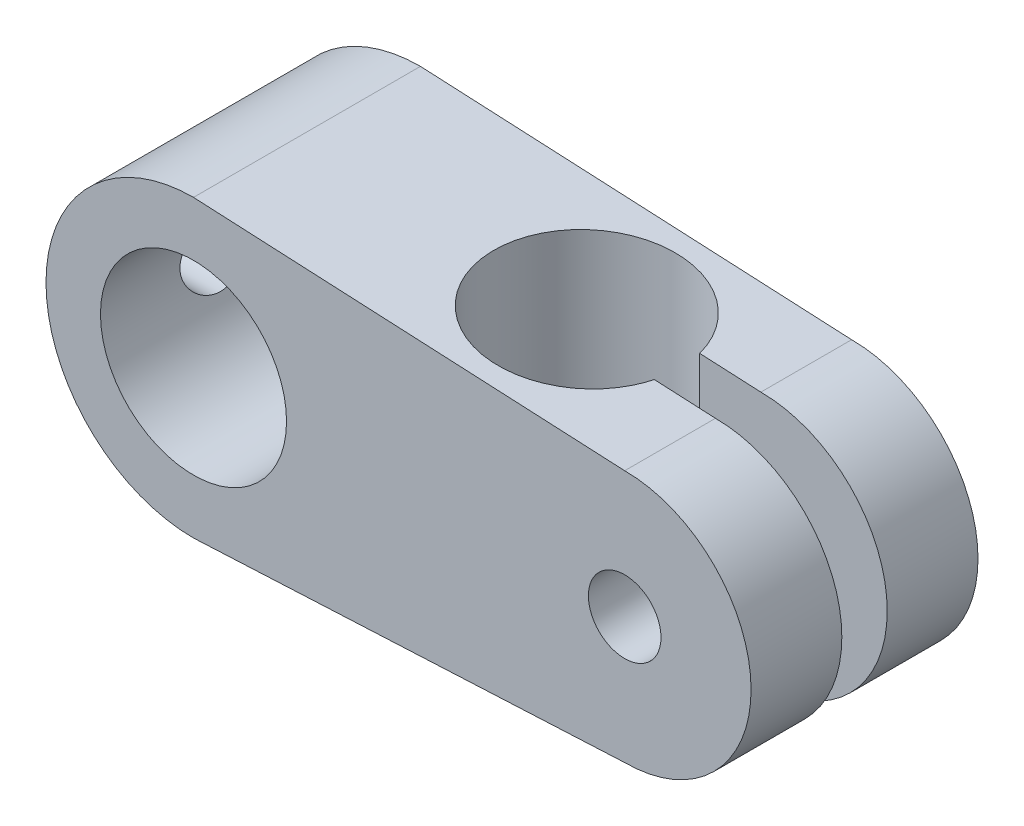
SolidWorks part; units mm, degrees
ref_plane "前视基准面" through (0, 0, 0) normal (0, 0, 1) x (1, 0, 0)
ref_plane "上视基准面" through (0, 0, 0) normal (0, 1, 0) x (1, 0, 0)
ref_plane "右视基准面" through (0, 0, 0) normal (1, 0, 0) x (0, 0, -1)
other "Configuration Table"
sketch "草图1" plane through (0, 0, 0) normal (0, 0, 1) x (1, 0, 0)
  line L0 (-10.3874, 0) -> (21.7322, 0) construction
  line L1 (0, 6.5) -> (19, 5.5688)
  line L2 (0, -6.5) -> (19, -5.5688)
  circle A0 centre (0, 0) radius 4.1
  arc A1 (0.6356, 6.4689) -> (0.6356, -6.4689) centre (0, 0) ccw
  arc A3 (19, -5.5688) -> (19, 5.5688) centre (19, 0) ccw
  dimension "D1" = 8.2
  dimension "D2" = 13
  dimension "D3" = 19
extrude "凸台-拉伸1" add sketch "草图1" along normal blind 10
sketch "草图2" plane through (0.3178, 6.4844, 0) normal (0.0489, 0.9988, 0) x (0.9988, -0.0489, 0)
  line L0 (-6.5, -5) -> (31.1524, -5) construction
  line L1 (-6.5, 0) -> (-6.5, -10) construction
sketch "草图6" plane through (0, 0, 0) normal (0, 1, 0) x (1, 0, 0)
  line L0 (-6.1744, -5) -> (31.4329, -5) construction
  circle A0 centre (12.3299, -5) radius 4.1
  point P4 (12.3299, -5)
  dimension "D1" = 8.2
extrude "切除-拉伸2" cut sketch "草图6" against normal mid plane 19
ref_plane "基准面1" through (0, 0, 5) normal (0, 0, 1) x (1, 0, 0)
sketch "草图10" plane through (0, 0, 5) normal (0, 0, 1) x (1, 0, 0)
  line L1 (12.2644, 9.3427) -> (29.314, 9.3427)
  line L2 (12.2644, 9.3427) -> (12.2644, -11.0198)
  line L3 (12.2644, -11.0198) -> (29.314, -11.0198)
  line L4 (29.314, 9.3427) -> (29.314, -11.0198)
extrude "切除-拉伸4" cut sketch "草图10" against normal mid plane 2
sketch "草图11" plane through (0, 0, 10) normal (0, 0, 1) x (1, 0, 0)
  circle A0 centre (19, 0) radius 1.6
  dimension "D1" = 3.2
extrude "切除-拉伸5" cut sketch "草图11" against normal mid plane 39
sketch "草图12" plane through (0, 0, 0) normal (1, 0, 0) x (0, 0, -1)
  circle A0 centre (-5, 0) radius 1.5
  dimension "D1" = 3
extrude "切除-拉伸6" cut sketch "草图12" against normal blind 39
